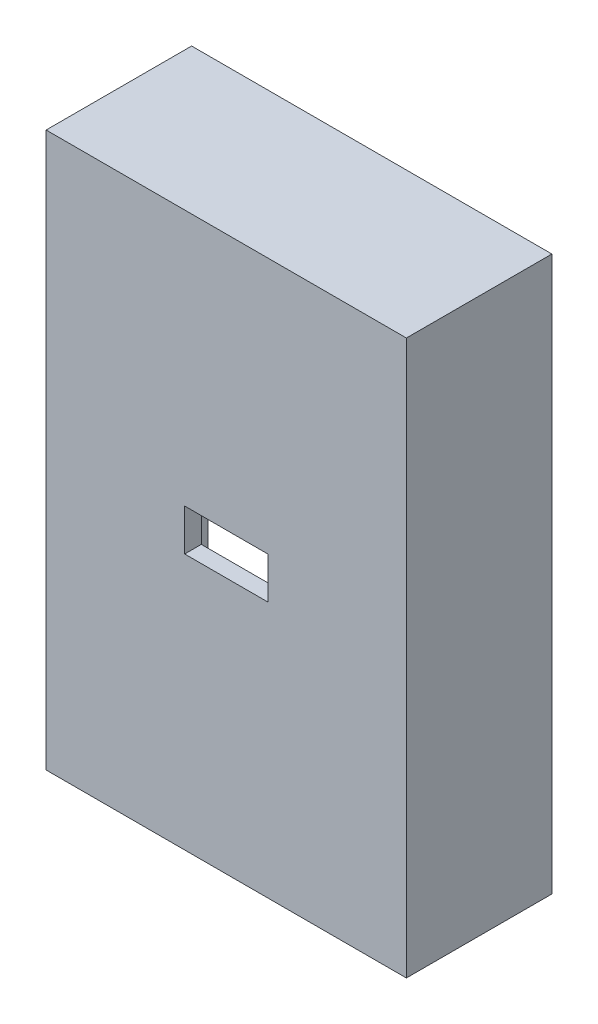
SolidWorks part; units mm, degrees
ref_plane "Front Plane" through (0, 0, 0) normal (0, 0, 1) x (1, 0, 0)
ref_plane "Top Plane" through (0, 0, 0) normal (0, 1, 0) x (1, 0, 0)
ref_plane "Right Plane" through (0, 0, 0) normal (1, 0, 0) x (0, 0, -1)
sketch "Sketch1" plane through (0, 0, 0) normal (0, 0, 1) x (1, 0, 0)
  line L1 (0, 0) -> (16, 0) construction
  line L2 (0, 0) -> (0, -16) construction
  line L3 (0, -16) -> (16, -16) construction
  line L4 (16, 0) -> (16, -16) construction
  line L5 (-5, 12) -> (21, 12)
  line L6 (-5, 12) -> (-5, -28)
  line L7 (-5, -28) -> (21, -28)
  line L8 (21, 12) -> (21, -28)
  line L9 (5, -6.5) -> (11, -6.5)
  line L10 (5, -6.5) -> (5, -9.5)
  line L11 (5, -9.5) -> (11, -9.5)
  line L12 (11, -6.5) -> (11, -9.5)
  point P4 (8, 12)
  point P10 (8, 0)
  point P15 (8, -6.5)
  point P16 (11, -8)
  point P17 (16, -8)
  dimension "D1" = 16
  dimension "D2" = 16
  dimension "D3" = 40
  dimension "D4" = 26
  dimension "D5" = 12
  dimension "D6" = 6
  dimension "D7" = 3
extrude "Boss-Extrude1" add sketch "Sketch1" along normal blind 1.2
sketch "Sketch2" plane through (0, 0, 0) normal (0, 0, -1) x (-1, 0, 0)
  line L0 (-11, -6.5) -> (-5, -6.5) construction
  line L1 (-16, 0) -> (0, 0)
  line L2 (-16, 0) -> (-16, -16)
  line L3 (-16, -16) -> (0, -16)
  line L4 (0, 0) -> (0, -16)
  line L5 (-5, -6.5) -> (-5, -9.5) construction
  line L10 (5, -28) -> (5, 12)
  line L11 (5, 12) -> (-21, 12)
  line L12 (-21, 12) -> (-21, -28)
  line L13 (-21, -28) -> (5, -28)
  line L14 (5, -28) -> (5, 12)
  line L15 (5, 12) -> (-21, 12)
  line L16 (-21, 12) -> (-21, -28)
  line L17 (-21, -28) -> (5, -28)
  point P4 (-8, 0)
  point P7 (-8, -6.5)
  point P8 (0, -8)
  point P11 (-5, -8)
  dimension "D1" = 16
  dimension "D2" = 0
extrude "Boss-Extrude2" add sketch "Sketch2" along normal blind 1.3
sketch "Sketch5" plane through (0, 0, -1.3) normal (0, 0, -1) x (-1, 0, 0)
  line L0 (-19.8, 10.8) -> (-19.8, -26.8)
  line L1 (-21, 12) -> (5, 12)
  line L2 (-21, 12) -> (-21, -28)
  line L3 (-21, -28) -> (5, -28)
  line L4 (5, 12) -> (5, -28)
  line L5 (-19.8, -26.8) -> (3.8, -26.8)
  line L6 (3.8, 10.8) -> (3.8, -26.8)
  line L7 (-19.8, 10.8) -> (3.8, 10.8)
  dimension "D1" = 1.2
extrude "Boss-Extrude3" add sketch "Sketch5" along normal blind 8
sketch "Sketch6" plane through (0, -28, 0) normal (0, -1, 0) x (1, 0, 0)
  line L0 (21, -9.3) -> (-5, -9.3) construction
  line L1 (21, 1.2) -> (21, -9.3) construction
  circle A0 centre (8, -4.05) radius 2
  point P2 (0, 0)
  point P5 (8, -9.3)
  point P6 (0, 0)
  point P9 (21, -4.05)
  dimension "D1" = 4
extrude "Cut-Extrude1" cut sketch "Sketch6" against normal blind 8
